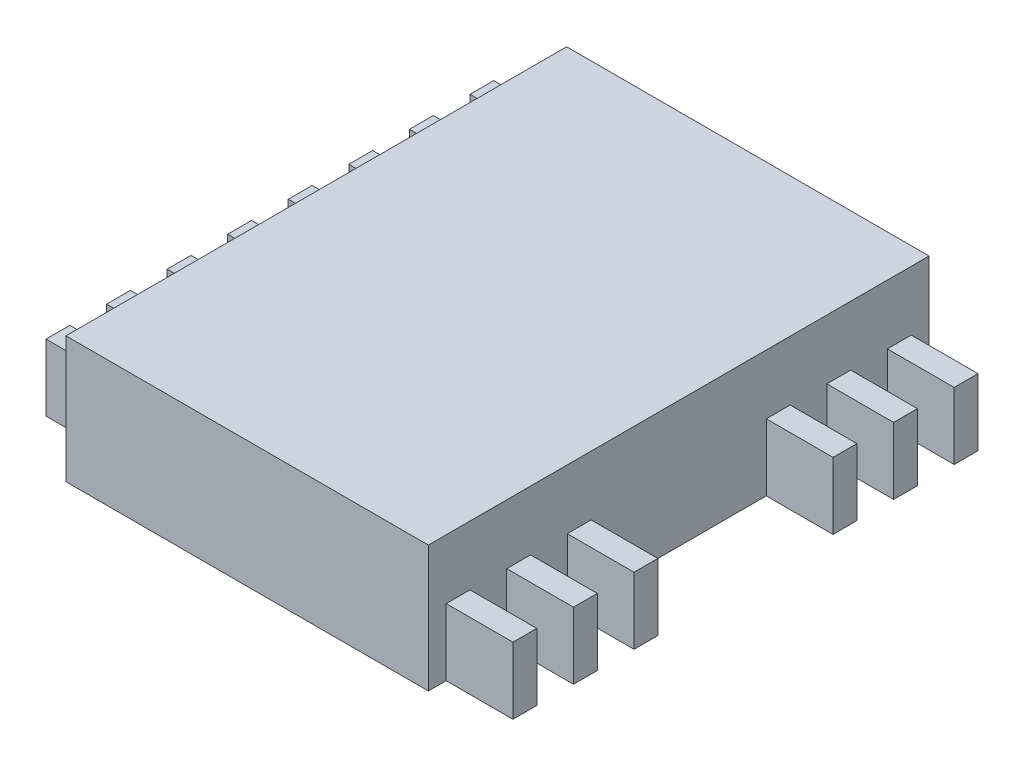
SolidWorks part; units mm, degrees
ref_plane "Front Plane" through (0, 0, 0) normal (0, 0, 1) x (1, 0, 0)
ref_plane "Top Plane" through (0, 0, 0) normal (0, 1, 0) x (1, 0, 0)
ref_plane "Right Plane" through (0, 0, 0) normal (1, 0, 0) x (0, 0, -1)
sketch "Sketch1" plane through (0, 0, 0) normal (0, 1, 0) x (1, 0, 0)
  line L1 (-3.8, -5.25) -> (3.8, -5.25)
  line L2 (-3.8, -5.25) -> (-3.8, 5.25)
  line L3 (-3.8, 5.25) -> (3.8, 5.25)
  line L4 (3.8, -5.25) -> (3.8, 5.25)
  line L5 (-3.8, -5.25) -> (3.8, 5.25) construction
  line L6 (-3.8, 5.25) -> (3.8, -5.25) construction
  point P0 (0, 0)
  dimension "D1" = 7.6
  dimension "D2" = 10.5
extrude "Boss-Extrude1" add sketch "Sketch1" along normal blind 2.65
sketch "Sketch2" plane through (-3.8, 0, 0) normal (-1, 0, 0) x (0, 0, 1)
  line L0 (-5.25, 0) -> (5.25, 0) construction
  line L1 (-5.1219, 0) -> (-4.6219, 0)
  line L2 (-5.1219, 0) -> (-5.1219, 1.4)
  line L3 (-5.1219, 1.4) -> (-4.6219, 1.4)
  line L4 (-4.6219, 0) -> (-4.6219, 1.4)
  line L5 (-3.8519, 1.4) -> (-3.3519, 1.4)
  line L6 (-3.3519, 0) -> (-3.3519, 1.4)
  line L7 (-3.8519, 0) -> (-3.8519, 1.4)
  line L8 (-3.8519, 0) -> (-3.3519, 0)
  line L9 (-2.5819, 1.4) -> (-2.0819, 1.4)
  line L10 (-2.0819, 0) -> (-2.0819, 1.4)
  line L11 (-2.5819, 0) -> (-2.5819, 1.4)
  line L12 (-2.5819, 0) -> (-2.0819, 0)
  line L13 (-1.3119, 1.4) -> (-0.8119, 1.4)
  line L14 (-0.8119, 0) -> (-0.8119, 1.4)
  line L15 (-1.3119, 0) -> (-1.3119, 1.4)
  line L16 (-1.3119, 0) -> (-0.8119, 0)
  line L17 (-0.0419, 1.4) -> (0.4581, 1.4)
  line L18 (0.4581, 0) -> (0.4581, 1.4)
  line L19 (-0.0419, 0) -> (-0.0419, 1.4)
  line L20 (-0.0419, 0) -> (0.4581, 0)
  line L21 (1.2281, 1.4) -> (1.7281, 1.4)
  line L22 (1.7281, 0) -> (1.7281, 1.4)
  line L23 (1.2281, 0) -> (1.2281, 1.4)
  line L24 (1.2281, 0) -> (1.7281, 0)
  line L25 (2.4981, 1.4) -> (2.9981, 1.4)
  line L26 (2.9981, 0) -> (2.9981, 1.4)
  line L27 (2.4981, 0) -> (2.4981, 1.4)
  line L28 (2.4981, 0) -> (2.9981, 0)
  line L29 (3.7681, 1.4) -> (4.2681, 1.4)
  line L30 (4.2681, 0) -> (4.2681, 1.4)
  line L31 (3.7681, 0) -> (3.7681, 1.4)
  line L32 (3.7681, 0) -> (4.2681, 0)
  dimension "D1" = 1.4
  dimension "D2" = 0.5
  dimension "D3" = 8
extrude "Boss-Extrude2" add sketch "Sketch2" along normal blind 1.4
sketch "Sketch4" plane through (3.8, 0, 0) normal (1, 0, 0) x (0, 0, -1)
  line L0 (-5.25, 0) -> (5.25, 0) construction
  line L1 (-4.8764, 0) -> (-4.3764, 0)
  line L2 (-4.8764, 0) -> (-4.8764, 1.4)
  line L3 (-4.8764, 1.4) -> (-4.3764, 1.4)
  line L4 (-4.3764, 0) -> (-4.3764, 1.4)
  line L5 (-3.6064, 0) -> (-3.1064, 0)
  line L6 (-3.1064, 0) -> (-3.1064, 1.4)
  line L7 (-3.6064, 1.4) -> (-3.1064, 1.4)
  line L8 (-3.6064, 0) -> (-3.6064, 1.4)
  line L9 (-2.3364, 0) -> (-1.8364, 0)
  line L10 (-1.8364, 0) -> (-1.8364, 1.4)
  line L11 (-2.3364, 1.4) -> (-1.8364, 1.4)
  line L12 (-2.3364, 0) -> (-2.3364, 1.4)
  line L13 (0, 0) -> (0, 1.1432) construction
  line L14 (2.3364, 0) -> (2.3364, 1.4)
  line L15 (2.3364, 1.4) -> (1.8364, 1.4)
  line L16 (1.8364, 0) -> (1.8364, 1.4)
  line L17 (2.3364, 0) -> (1.8364, 0)
  line L18 (3.6064, 0) -> (3.6064, 1.4)
  line L19 (3.6064, 1.4) -> (3.1064, 1.4)
  line L20 (3.1064, 0) -> (3.1064, 1.4)
  line L21 (3.6064, 0) -> (3.1064, 0)
  line L22 (4.3764, 0) -> (4.3764, 1.4)
  line L23 (4.8764, 1.4) -> (4.3764, 1.4)
  line L24 (4.8764, 0) -> (4.8764, 1.4)
  line L25 (4.8764, 0) -> (4.3764, 0)
  dimension "D1" = 0.5
  dimension "D2" = 1.4
  dimension "D3" = 3
extrude "Boss-Extrude3" add sketch "Sketch4" along normal blind 1.4
